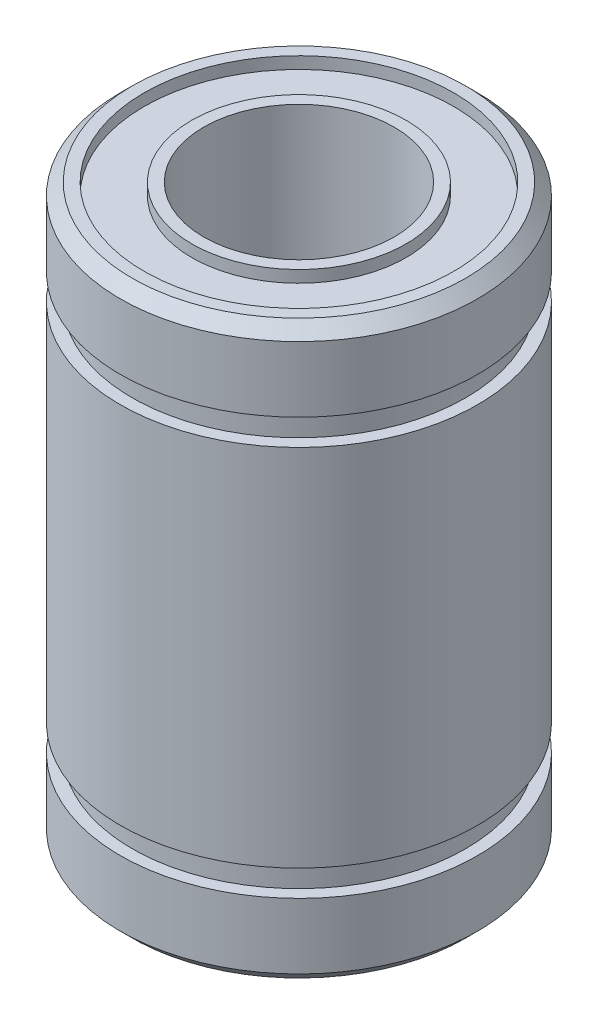
SolidWorks part; units mm, degrees
ref_plane "Front Plane" through (0, 0, 0) normal (0, 0, 1) x (1, 0, 0)
ref_plane "Top Plane" through (0, 0, 0) normal (0, 1, 0) x (1, 0, 0)
ref_plane "Right Plane" through (0, 0, 0) normal (1, 0, 0) x (0, 0, -1)
sketch "Sketch1" plane through (0, 0, 0) normal (0, 0, 1) x (1, 0, 0)
  line L0 (0, 12) -> (0, 0) construction
  line L1 (0, 0) -> (0, -12) construction
  line L2 (0, 12) -> (4, 12) construction
  line L3 (0, -12) -> (4, -12) construction
  line L4 (4, -12) -> (4, 12)
  line L5 (4, 12) -> (7, 12)
  line L6 (7, 12) -> (7.5, 11.5)
  line L7 (7.5, 11.5) -> (7.5, 8.75)
  line L8 (7.5, 7.65) -> (7.5, 8.75) construction
  line L9 (7.5, -8.75) -> (7.5, -7.65) construction
  line L10 (7.5, 7.65) -> (7.5, -7.65)
  line L11 (7.5, -11.5) -> (7, -11.5) construction
  line L12 (7, -11.5) -> (7, -12) construction
  line L13 (7.5, -8.75) -> (7.5, -11.5)
  line L14 (7.5, -11.5) -> (7, -12)
  line L15 (7, -12) -> (4, -12)
  line L16 (7.5, 11.5) -> (7, 11.5) construction
  line L17 (7, 11.5) -> (7, 12) construction
  line L18 (7, -11.5) -> (7, 11.5) construction
  line L19 (7.5525, -8.2) -> (7.5525, 8.2) construction
  line L20 (7, -8.2) -> (7.5525, -8.2) construction
  line L21 (7.5, 8.75) -> (7, 8.75)
  line L22 (0, 0) -> (7.5, 0) construction
  line L23 (7, 8.75) -> (7, 7.65)
  line L24 (7, 7.65) -> (7.5, 7.65)
  line L25 (7.5, -7.65) -> (7, -7.65)
  line L26 (7, -7.65) -> (7, -8.75)
  line L27 (7, -8.75) -> (7.5, -8.75)
  arc A0 (7.5, 8.75) -> (7.5, 7.65) centre (7.5525, 8.2) ccw construction
  arc A1 (7.5, -7.65) -> (7.5, -8.75) centre (7.5525, -8.2) ccw construction
  dimension "Total_length" = 24
  dimension "Inside_diameter" = 8
  dimension "D4" = 0.5
  dimension "Distance_between_lockingrings" = 17.5
  dimension "Diameter_outside" = 15
  dimension "Locking_ring_width" = 1.1
  dimension "Locking_ring_groove_dia" = 14
revolve "Revolve1" add sketch "Sketch1" angle 360 about L0
sketch "Sketch2" plane through (0, 12, 0) normal (0, 1, 0) x (1, 0, 0)
  circle A0 centre (0, 0) radius 4.5
  circle A1 centre (0, 0) radius 6.5
  circle A2 centre (0, 0) radius 7.5 construction
  circle A3 centre (0, 0) radius 4 construction
  dimension "D1" = 1
  dimension "D2" = 0.5
extrude "Cut-Extrude1" cut sketch "Sketch2" against normal blind 0.5
mirror "Mirror1" about plane through (0, 0, 0) normal (0, 1, 0) of "Cut-Extrude1"
sketch "Sketch3" plane through (0, -11.5, 0) normal (0, -1, 0) x (1, 0, 0)
  line L0 (6.5, 0) -> (4.5, 0) construction
  circle A0 centre (0, 0) radius 5.1 construction
  circle A2 centre (0, 0) radius 6.5 construction
  circle A3 centre (0, 0) radius 4.5 construction
  text T0 "LM16UU" font "Century Gothic" height 0.8
  point P11 (5.5, 0)
  dimension "D1" = 0.4
split line "Split Line1"
